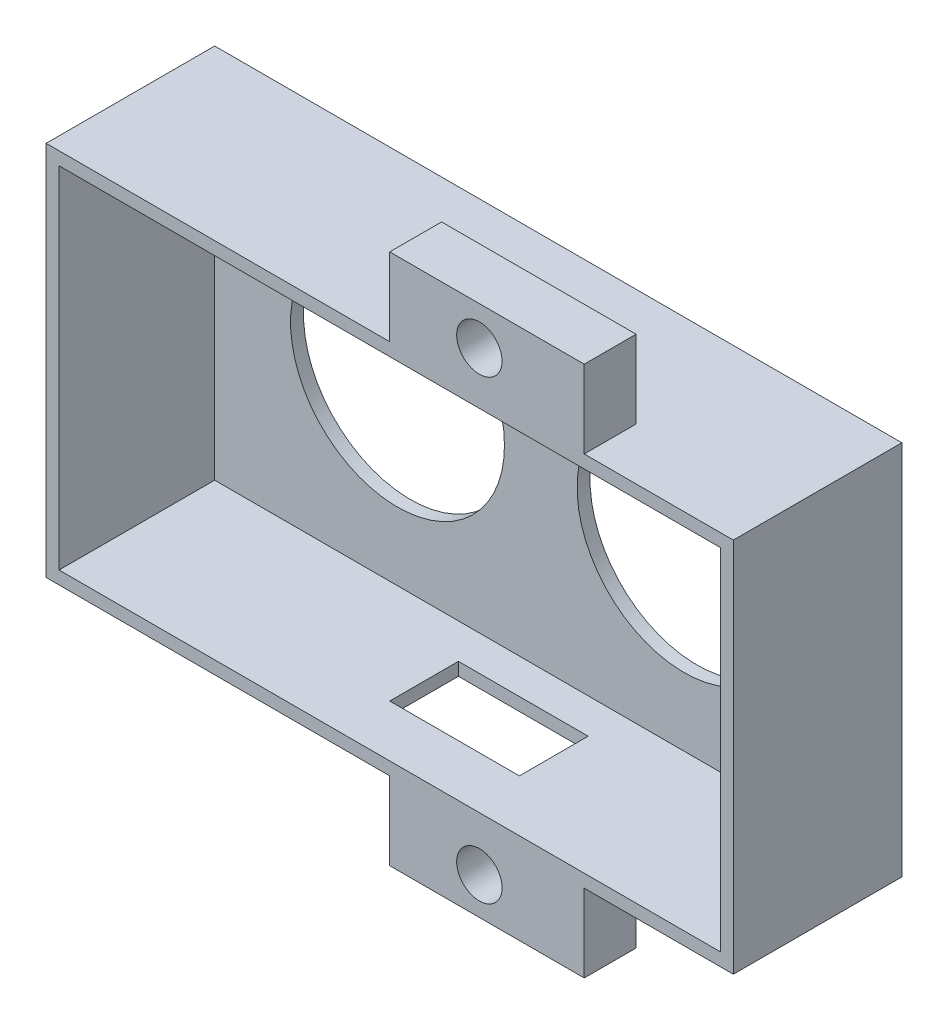
SolidWorks part; units mm, degrees
ref_plane "Front Plane" through (0, 0, 0) normal (0, 0, 1) x (1, 0, 0)
ref_plane "Top Plane" through (0, 0, 0) normal (0, 1, 0) x (1, 0, 0)
ref_plane "Right Plane" through (0, 0, 0) normal (1, 0, 0) x (0, 0, -1)
sketch "Sketch1" plane through (0, 0, 0) normal (0, 0, 1) x (1, 0, 0)
  line L1 (-26.5, -14.5) -> (26.5, -14.5)
  line L2 (-26.5, -14.5) -> (-26.5, 14.5)
  line L3 (-26.5, 14.5) -> (26.5, 14.5)
  line L4 (26.5, -14.5) -> (26.5, 14.5)
  line L5 (-26.5, -14.5) -> (26.5, 14.5) construction
  line L6 (-26.5, 14.5) -> (26.5, -14.5) construction
  point P0 (0, 0)
  dimension "D1" = 29
  dimension "D2" = 53
extrude "Boss-Extrude2" add sketch "Sketch1" along normal blind 13
shell "Shell5" thickness 1
sketch "Sketch3" plane through (0, 0, 1) normal (0, 0, 1) x (1, 0, 0)
  line L0 (-25.5, 13.5) -> (-25.5, -13.5) construction
  line L4 (25.5, -13.5) -> (25.5, 13.5) construction
  circle A0 centre (-11.4, 0) radius 8.25
  circle A1 centre (10.7, 0) radius 8.25
  dimension "D1" = 16.5
  dimension "D2" = 16.5
  dimension "D3" = 22.1
  dimension "D4" = 14.1
  dimension "D6" = 14.8
extrude "Cut-Extrude1" cut sketch "Sketch3" against normal blind 13
sketch "Sketch4" plane through (0, -14.5, 0) normal (0, -1, 0) x (1, 0, 0)
  line L0 (26.5, 13) -> (26.5, 0) construction
  line L1 (-4, 9) -> (6, 9)
  line L2 (-4, 9) -> (-4, 3.7)
  line L3 (-4, 3.7) -> (6, 3.7)
  line L4 (6, 9) -> (6, 3.7)
  line L5 (-4, 9) -> (6, 3.7) construction
  line L6 (-4, 3.7) -> (6, 9) construction
  line L7 (-26.5, 13) -> (26.5, 13) construction
  point P0 (1, 6.35)
  dimension "D1" = 10
  dimension "D2" = 5.3
  dimension "D3" = 30.5
  dimension "D4" = 4
extrude "Cut-Extrude2" cut sketch "Sketch4" against normal blind 13
sketch "Sketch5" plane through (0, 0, 13) normal (0, 0, 1) x (1, 0, 0)
  line L0 (26.5, 14.5) -> (-26.5, 14.5) construction
  line L1 (0, 14.5) -> (15, 14.5)
  line L2 (0, 14.5) -> (0, 20.5)
  line L3 (0, 20.5) -> (15, 20.5)
  line L4 (15, 14.5) -> (15, 20.5)
  line L5 (-26.5, -14.5) -> (26.5, -14.5) construction
  line L6 (0, -14.5) -> (15, -14.5)
  line L7 (0, -14.5) -> (0, -20.5)
  line L8 (0, -20.5) -> (15, -20.5)
  line L9 (15, -14.5) -> (15, -20.5)
  dimension "D1" = 15
  dimension "D2" = 6
  dimension "D3" = 15
  dimension "D4" = 6
extrude "Boss-Extrude3" add sketch "Sketch5" against normal blind 4
sketch "Sketch6" plane through (0, 0, 13) normal (0, 0, 1) x (1, 0, 0)
  circle A0 centre (6.9148, 17.5337) radius 1.75
  circle A1 centre (6.9148, -17.6471) radius 1.75
  point P4 (6.9148, -17.6471)
  dimension "D1" = 3.5
  dimension "D2" = 3.5
extrude "Cut-Extrude3" cut sketch "Sketch6" against normal blind 6
